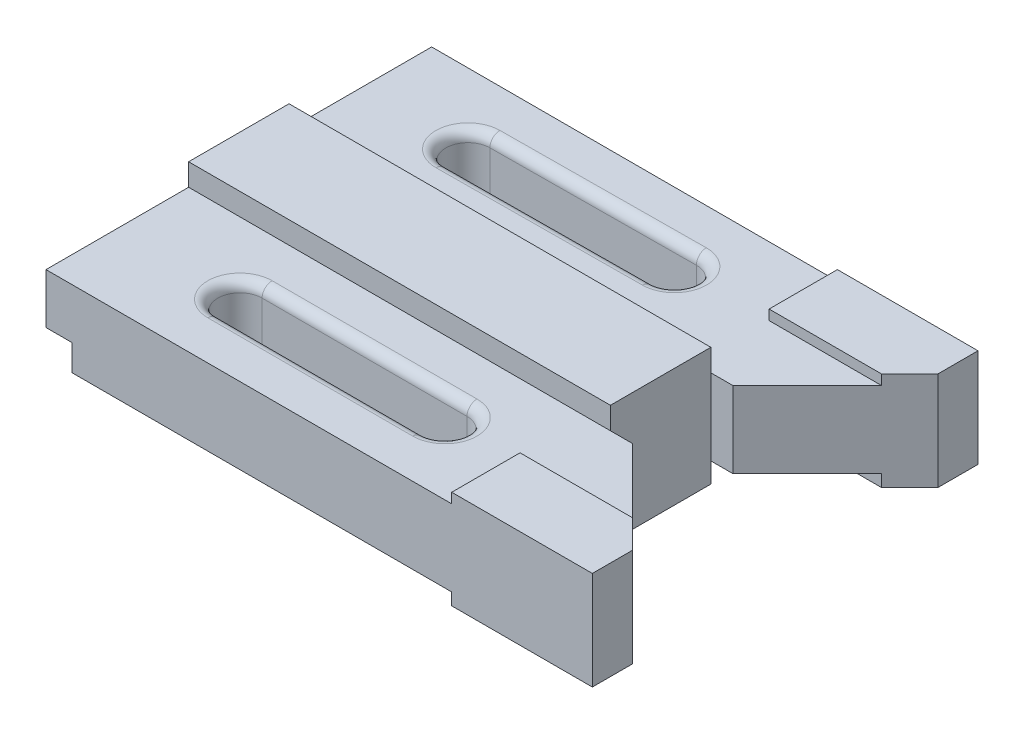
SolidWorks part; units mm, degrees
ref_plane "Front Plane" through (0, 0, 0) normal (0, 0, 1) x (1, 0, 0)
ref_plane "Top Plane" through (0, 0, 0) normal (0, 1, 0) x (1, 0, 0)
ref_plane "Right Plane" through (0, 0, 0) normal (1, 0, 0) x (0, 0, -1)
sketch "Sketch1" plane through (0, 0, 0) normal (0, 1, 0) x (1, 0, 0)
  line L0 (0, 0) -> (136, 0)
  line L1 (136, 0) -> (136, -10)
  line L2 (136, -10) -> (110.5, -35.5)
  line L3 (110.5, -35.5) -> (0, -35.5)
  line L4 (0, -35.5) -> (0, 0)
  line L5 (94, 0) -> (94, -17)
  line L6 (94, -17) -> (129, -17)
  line L7 (0, -60.5) -> (0, -96)
  line L8 (26.5421, -17.5) -> (77.5421, -17.1097) construction
  line L9 (26.5, -12.0002) -> (77.5, -11.6099)
  line L10 (26.5842, -22.9998) -> (77.5842, -22.6095)
  line L11 (0, -35.5) -> (105, -35.5)
  line L12 (0, -35.5) -> (0, -60.5)
  line L13 (0, -60.5) -> (105, -60.5)
  line L14 (105, -35.5) -> (105, -60.5)
  line L15 (0, -96) -> (136, -96)
  line L16 (136, -96) -> (136, -86)
  line L17 (105, -60.5) -> (110.5, -60.5)
  line L18 (110.5, -60.5) -> (136, -86)
  line L19 (94, -79) -> (129, -79)
  line L20 (30.5421, -78.25) -> (81.5421, -78.25) construction
  line L21 (30.5421, -72.75) -> (81.5421, -72.75)
  line L22 (30.5421, -83.75) -> (81.5421, -83.75)
  line L23 (94, -96) -> (94, -79)
  line L25 (0, 0) -> (-4, 0)
  line L26 (0, 0) -> (0, -96)
  line L27 (0, -96) -> (-4, -96)
  line L28 (-4, 0) -> (-4, -96)
  arc A0 (26.5, -12.0002) -> (26.5842, -22.9998) centre (26.5421, -17.5) ccw
  arc A1 (77.5842, -22.6095) -> (77.5, -11.6099) centre (77.5421, -17.1097) ccw
  arc A2 (30.5421, -72.75) -> (30.5421, -83.75) centre (30.5421, -78.25) ccw
  arc A3 (81.5421, -83.75) -> (81.5421, -72.75) centre (81.5421, -78.25) ccw
  point P12 (52.0421, -17.3048)
  point P27 (56.0421, -78.25)
  dimension "D8" = 5.5
  dimension "D17" = 5.5
  dimension "D1" = 35.5
  dimension "D2" = 45
  dimension "D3" = 10
  dimension "D4" = 140
  dimension "D5" = 35
  dimension "D6" = 17
  dimension "D7" = 51
  dimension "D9" = 30.5
  dimension "D10" = 17.5
  dimension "D11" = 25
  dimension "D12" = 105
  dimension "D13" = 35.5
  dimension "D14" = 140
  dimension "D15" = 10
  dimension "D16" = 45
  dimension "D18" = 51
  dimension "D19" = 17
  dimension "D20" = 96
  dimension "D21" = 4
extrude "Boss-Extrude4" add sketch "Sketch1" along normal blind 19 contours L5 L6 L2 L1 L0 | L6 L5 L0 L4 L3 L2 A1 L10 A0 L9 | L14 L3 L12 L13 | L15 L23 L19 L18 L17 L13 L7 A3 L22 A2 L21 | L23 L15 L16 L18 L19
sketch "Sketch4" plane through (0, 19, 0) normal (0, 1, 0) x (1, 0, 0)
  line L0 (94, 0) -> (94, -17)
  line L1 (0, 0) -> (136, 0) construction
  line L2 (94, -17) -> (129, -17)
  line L3 (136, -10) -> (110.5, -35.5) construction
  line L4 (0, -48) -> (105, -48) construction
  line L5 (0, -96) -> (0, 0) construction
  line L6 (105, -35.5) -> (105, -60.5) construction
  line L7 (94, -96) -> (94, -79)
  line L8 (94, -79) -> (129, -79)
  line L9 (105, -35.5) -> (0, -35.5)
  line L10 (105, -60.5) -> (0, -60.5)
  line L11 (0, -35.5) -> (0, -60.5)
  line L12 (105, -35.5) -> (105, -60.5)
  line M11 (0, 0) -> (0, -96)
  line M16 (105, -60.5) -> (105, -35.5)
  dimension "D1" = 35
  dimension "D2" = 17
extrude "Boss-Extrude5" add sketch "Sketch4" along normal blind 5.5 and the other way blind 24 contours L4 L12 L9 M11 | L4 L11 L10 M16
fillet "Fillet3" radius 2.5 16 edges at (25.0421, 0, 78.25) (25.0421, 19, 78.25) (56.0421, 0, 72.75) (56.0421, 19, 72.75) (87.0421, 0, 78.25) (87.0421, 19, 78.25) (21.0423, 0, 17.5421) (21.0423, 19, 17.5421) (52, 0, 11.805) (52, 19, 11.805) (83.0419, 0, 17.0676) (83.0419, 19, 17.0676) (56.0421, 0, 83.75) (56.0421, 19, 83.75) (52.0842, 0, 22.8047) (52.0842, 19, 22.8047)
sketch "Sketch5" plane through (0, 19, 0) normal (0, 1, 0) x (1, 0, 0)
  line L0 (101, 0) -> (101, -17)
  line L1 (0, 0) -> (136, 0) construction
  line L2 (101, -17) -> (129, -17)
  line L3 (136, -10) -> (110.5, -35.5) construction
  line L4 (0, -48) -> (105, -48) construction
  line L5 (0, -35.5) -> (0, -60.5) construction
  line L6 (105, -60.5) -> (105, -35.5) construction
  line L7 (101, 0) -> (136, 0)
  line L8 (136, 0) -> (136, -10)
  line L9 (136, -10) -> (129, -17)
  line L10 (136, -86) -> (129, -79)
  line L11 (101, -79) -> (129, -79)
  line L12 (101, -96) -> (101, -79)
  line L13 (101, -96) -> (136, -96)
  line L14 (136, -96) -> (136, -86)
  dimension "D1" = 17
  dimension "D2" = 35
  dimension "D3" = 135
extrude "Boss-Extrude7" add sketch "Sketch5" along normal blind 2.5 and the other way blind 22
sketch "Sketch7" plane through (0, 0, 96) normal (0, 0, 1) x (1, 0, 0)
  line L0 (0, 6.5) -> (6.5, 6.5)
  line L1 (0, 19) -> (0, 0) construction
  line L2 (6.5, 6.5) -> (6.5, -5)
  line L3 (105, -5) -> (0, -5) construction
  line L4 (0, 6.5) -> (0, -5)
  line L5 (0, -5) -> (6.5, -5)
  dimension "D1" = 6.5
  dimension "D2" = 11.5
extrude "Cut-Extrude1" cut sketch "Sketch7" against normal blind 96
equation "\"a\"= 140mm"
equation "\"b\"= 51mm"
equation "\"c\"= 45deg"
